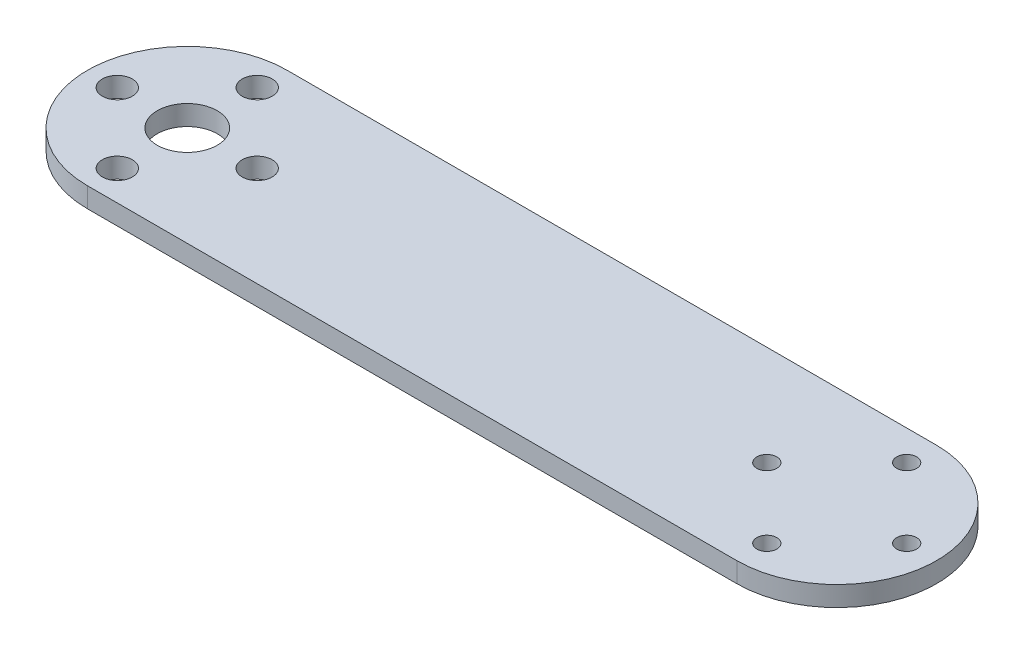
SolidWorks part; units mm, degrees
ref_plane "Спереди" through (0, 0, 0) normal (0, 0, 1) x (1, 0, 0)
ref_plane "Сверху" through (0, 0, 0) normal (0, 1, 0) x (1, 0, 0)
ref_plane "Справа" through (0, 0, 0) normal (1, 0, 0) x (0, 0, -1)
sketch "Эскиз1" plane through (0, 0, 0) normal (0, 1, 0) x (1, 0, 0)
  line L0 (0, 10) -> (65, 10)
  line L1 (0, -10) -> (65, -10)
  arc A0 (0, 10) -> (0, -10) centre (0, 0) ccw
  circle A1 centre (0, 0) radius 7 construction
  circle A2 centre (0, 0) radius 8.5 construction
  circle A3 centre (0, 7) radius 1.5
  circle A4 centre (7, 0) radius 1.5
  circle A5 centre (0, -7) radius 1.5
  circle A6 centre (-7, 0) radius 1.5
  arc A7 (65, -10) -> (65, 10) centre (65, 0) ccw
  circle A8 centre (65, 0) radius 7 construction
  circle A9 centre (65, 0) radius 8 construction
  circle A10 centre (65, 7) radius 1
  circle A11 centre (72, 0) radius 1
  circle A12 centre (65, -7) radius 1
  circle A13 centre (58, 0) radius 1
  circle A14 centre (0, 0) radius 3
  dimension "D1" = 14
  dimension "D2" = 17
  dimension "D3" = 20
  dimension "D4" = 16
  dimension "D5" = 14
  dimension "D7" = 6
  dimension "D8" = 10
  dimension "D6" = 65
extrude "Бобышка-Вытянуть1" add sketch "Эскиз1" along normal blind 2
